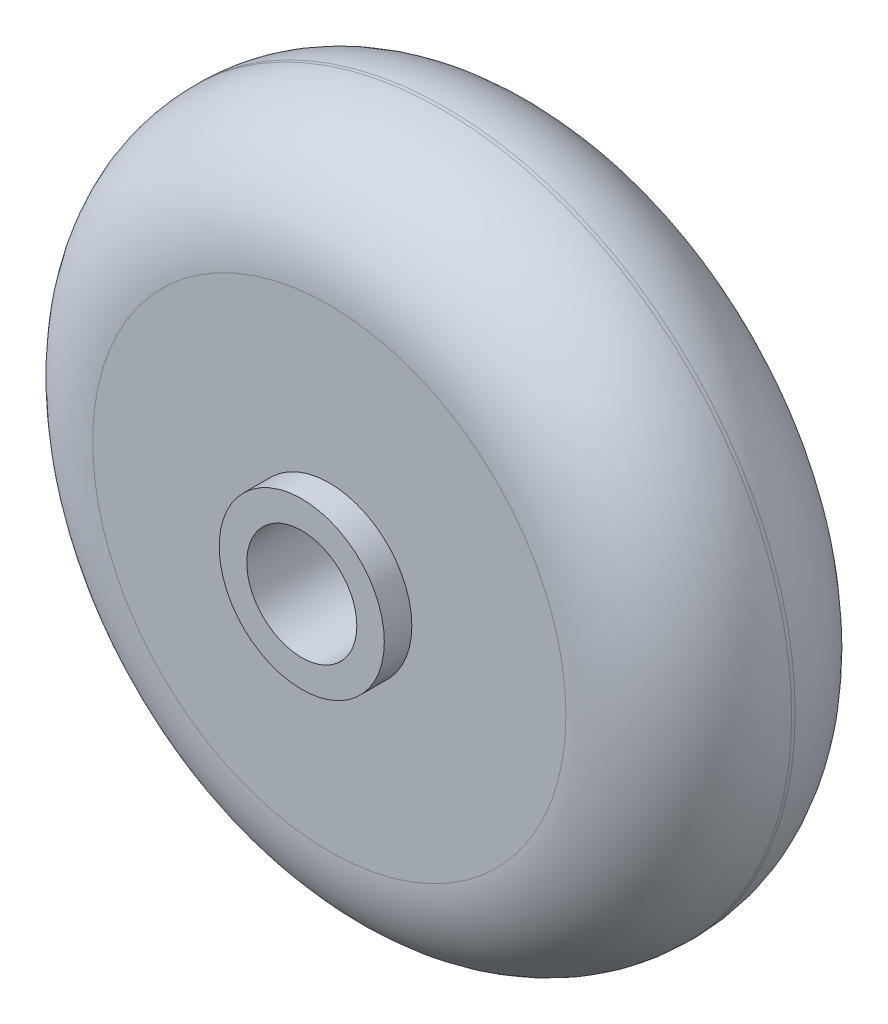
SolidWorks part; units mm, degrees
ref_plane "Plan de face" through (0, 0, 0) normal (0, 0, 1) x (1, 0, 0)
ref_plane "Plan de dessus" through (0, 0, 0) normal (0, 1, 0) x (1, 0, 0)
ref_plane "Plan de droite" through (0, 0, 0) normal (1, 0, 0) x (0, 0, -1)
sketch "Esquisse1" plane through (0, 0, 0) normal (0, 0, 1) x (1, 0, 0)
  circle A0 centre (0, 0) radius 25.4
  circle A1 centre (0, 0) radius 4
  dimension "D1" = 8
  dimension "D2" = 50.8
extrude "Boss.-Extru.1" add sketch "Esquisse1" along normal blind 16.66
sketch "Esquisse2" plane through (0, 0, 16.66) normal (0, 0, 1) x (1, 0, 0)
  circle A0 centre (0, 0) radius 6
  circle A1 centre (0, 0) radius 4
extrude "Boss.-Extru.2" add sketch "Esquisse2" along normal blind 2 and the other way offset from surface (18.66 mm away) 2 other way up to face at (25.4, 0, 0)
fillet "Congé1" radius 8.2 2 edges at (25.4, 0, 0) (25.4, 0, 16.66)
